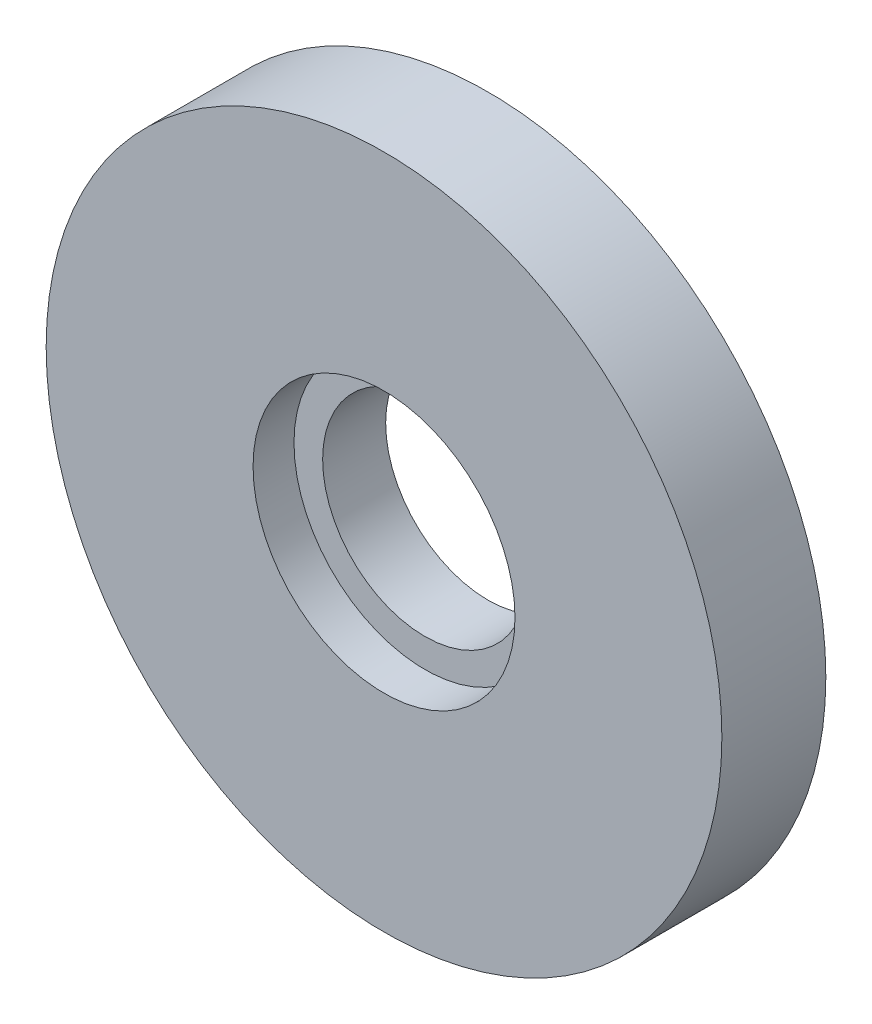
SolidWorks part; units mm, degrees
ref_plane "Front Plane" through (0, 0, 0) normal (0, 0, 1) x (1, 0, 0)
ref_plane "Top Plane" through (0, 0, 0) normal (0, 1, 0) x (1, 0, 0)
ref_plane "Right Plane" through (0, 0, 0) normal (1, 0, 0) x (0, 0, -1)
sketch "Sketch1" plane through (0, 0, 0) normal (0, 0, 1) x (1, 0, 0)
  circle A0 centre (0, 0) radius 41.275
extrude "Boss-Extrude1" add sketch "Sketch1" along normal mid plane 12.7
sketch "Sketch2" plane through (0, 0, 6.35) normal (0, 0, 1) x (1, 0, 0)
  line L0 (0, 37.0439) -> (0, -33.4409) construction
  line L1 (-40.8265, 0) -> (40.1198, 0) construction
  circle A0 centre (0, 0) radius 12.5
extrude "Cut-Extrude1" cut sketch "Sketch2" against normal through all and the other way through all
sketch "Sketch3" plane through (0, 0, 6.35) normal (0, 0, 1) x (1, 0, 0)
  circle A0 centre (0, 0) radius 16
extrude "Cut-Extrude2" cut sketch "Sketch3" against normal blind 5
